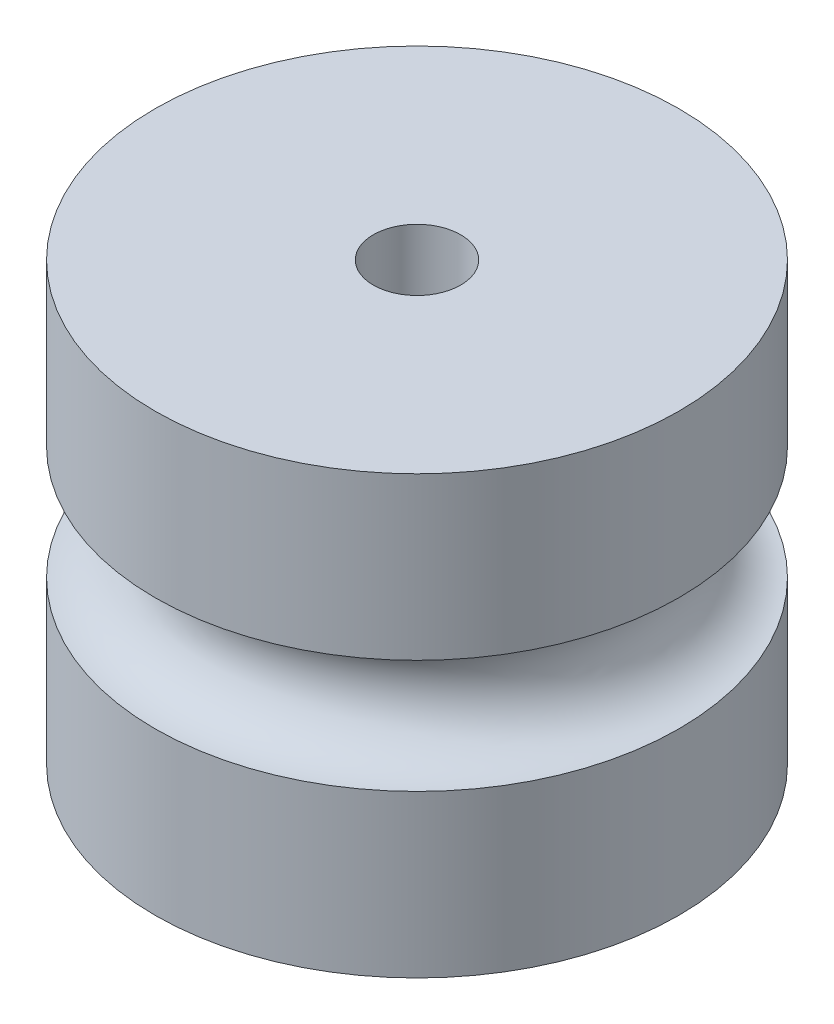
SolidWorks part; units mm, degrees
material "6063-T5"
ref_plane "Front Plane" through (0, 0, 0) normal (0, 0, 1) x (1, 0, 0)
ref_plane "Top Plane" through (0, 0, 0) normal (0, 1, 0) x (1, 0, 0)
ref_plane "Right Plane" through (0, 0, 0) normal (1, 0, 0) x (0, 0, -1)
sketch "Sketch1" plane through (0, 0, 0) normal (0, 1, 0) x (1, 0, 0)
  circle A0 centre (0, 0) radius 3
  circle A1 centre (0, 0) radius 0.5
  dimension "D1" = 6
  dimension "D2" = 1
extrude "Boss-Extrude1" add sketch "Sketch1" along normal blind 5
sketch "Sketch2" plane through (0, 0, 0) normal (0, 0, 1) x (1, 0, 0)
  line L0 (3, 0) -> (3, 5) construction
  line L1 (0, 0) -> (0, 5) construction
  line L2 (0.5, 5) -> (-0.5, 5) construction
  circle A0 centre (3, 2.5) radius 0.65
  dimension "D1" = 1.3
revolve "Cut-Revolve1" cut sketch "Sketch2" angle 360 about L1
